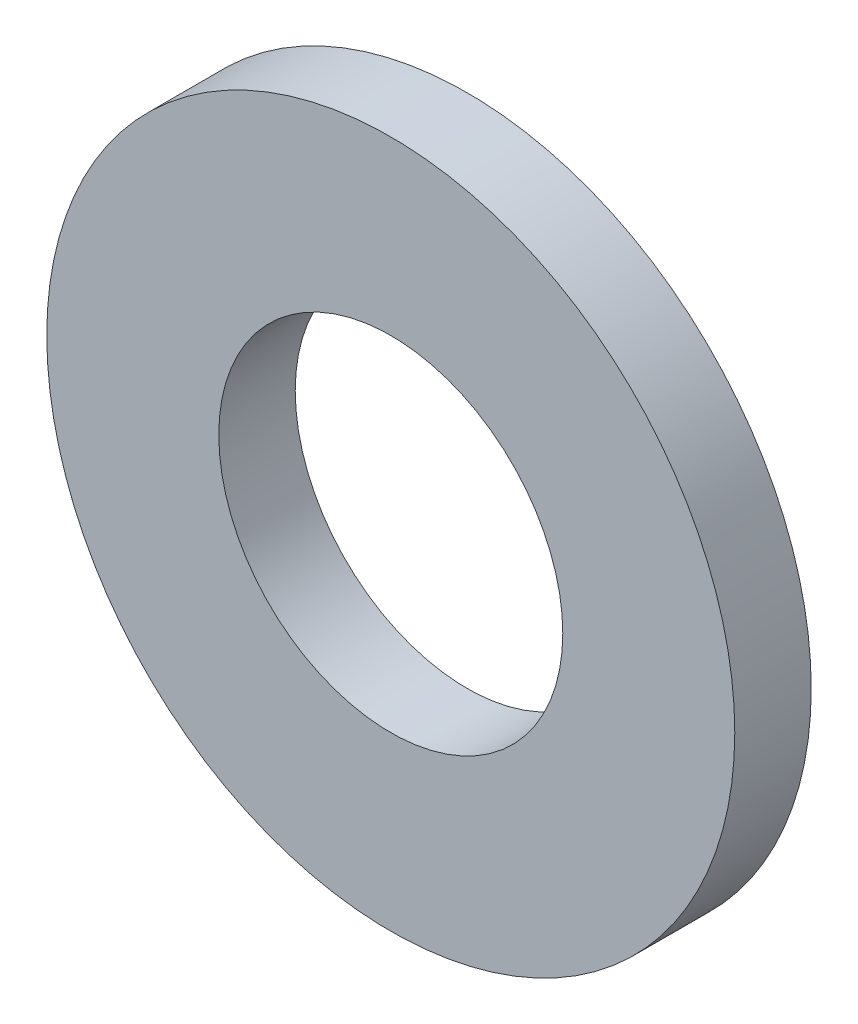
SolidWorks part; units mm, degrees
ref_plane "前视基准面" through (0, 0, 0) normal (0, 0, 1) x (1, 0, 0)
ref_plane "上视基准面" through (0, 0, 0) normal (0, 1, 0) x (1, 0, 0)
ref_plane "右视基准面" through (0, 0, 0) normal (1, 0, 0) x (0, 0, -1)
sketch "草图1" plane through (0, 0, 0) normal (0, 0, 1) x (1, 0, 0)
  circle A0 centre (0, 0) radius 4.5
  dimension "D1" = 9
extrude "金属件无牙型包络" add sketch "草图1" along normal blind 1
sketch "草图2" plane through (0, 0, 0) normal (0, 0, 1) x (1, 0, 0)
  circle A0 centre (0, 0) radius 2.25
  dimension "D1" = 4.5
extrude "内孔_装配间隙" cut sketch "草图2" along normal blind 1
